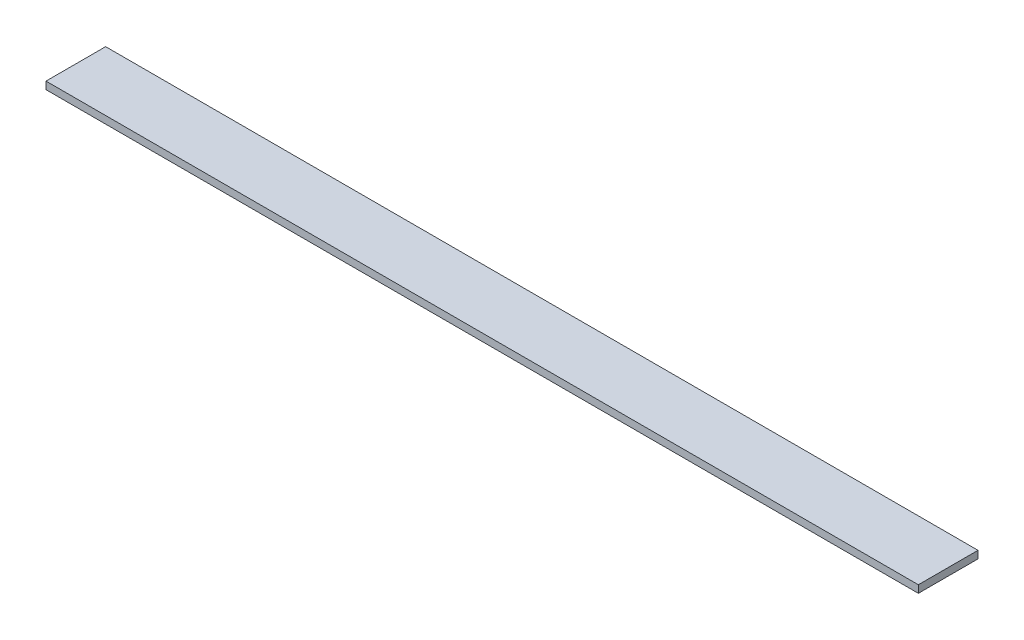
SolidWorks part; units mm, degrees
ref_plane "Front Plane" through (0, 0, 0) normal (0, 0, 1) x (1, 0, 0)
ref_plane "Top Plane" through (0, 0, 0) normal (0, 1, 0) x (1, 0, 0)
ref_plane "Right Plane" through (0, 0, 0) normal (1, 0, 0) x (0, 0, -1)
sketch "Sketch1" plane through (0, 0, 0) normal (0, 1, 0) x (1, 0, 0)
  line L2 (-371.475, 25.4) -> (371.475, 25.4)
  line L3 (-371.475, 25.4) -> (-371.475, -25.4)
  line L4 (-371.475, -25.4) -> (371.475, -25.4)
  line L5 (371.475, 25.4) -> (371.475, -25.4)
  line L6 (-371.475, 25.4) -> (371.475, -25.4) construction
  line L7 (-371.475, -25.4) -> (371.475, 25.4) construction
  point P1 (0, 0)
  dimension "D1" = 50.8
  dimension "D2" = 742.95
extrude "Boss-Extrude1" add sketch "Sketch1" along normal blind 6.35
